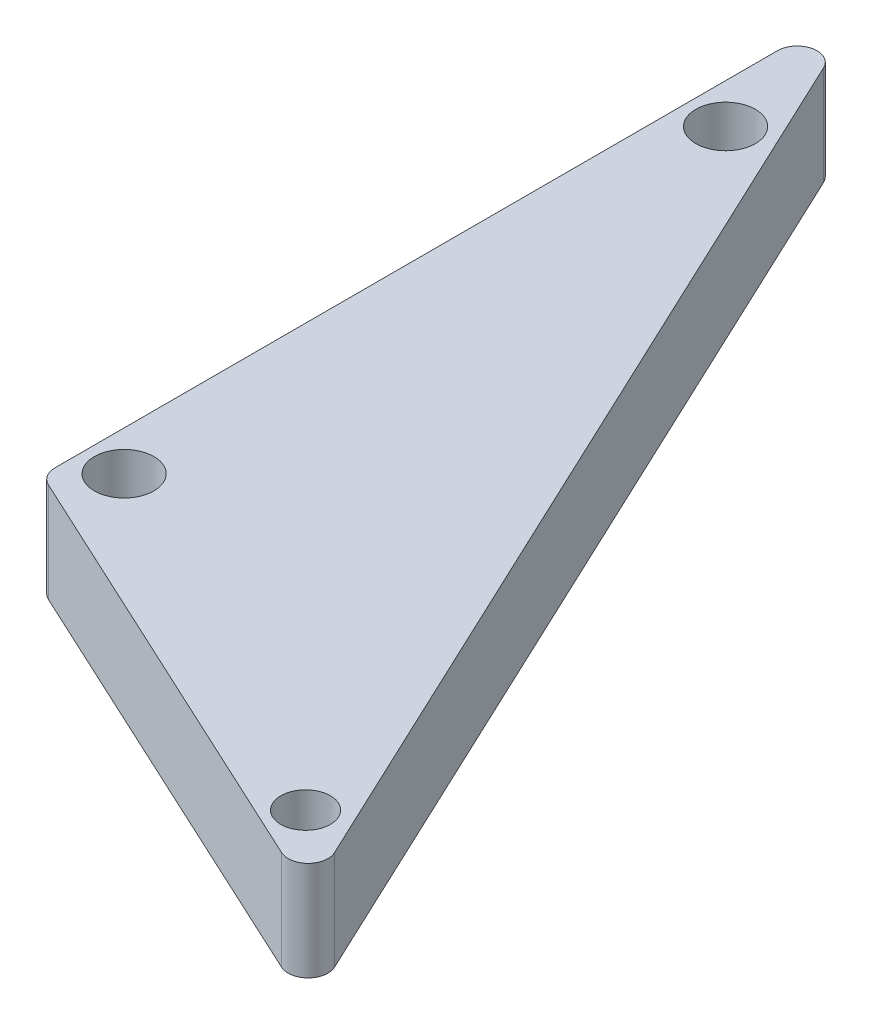
SolidWorks part; units mm, degrees
ref_plane "Front Plane" through (0, 0, 0) normal (0, 0, 1) x (1, 0, 0)
ref_plane "Top Plane" through (0, 0, 0) normal (0, 1, 0) x (1, 0, 0)
ref_plane "Right Plane" through (0, 0, 0) normal (1, 0, 0) x (0, 0, -1)
sketch "Sketch1" plane through (0, 0, 0) normal (0, 1, 0) x (1, 0, 0)
  line L0 (0, 0) -> (0, 105.41)
  line L3 (0, 0) -> (0, -29.464) construction
  line L4 (0, -29.464) -> (63.5, -29.464) construction
  line L5 (0, 105.41) -> (63.5, -29.464)
  line L6 (63.5, -29.464) -> (0, 0)
  dimension "D1" = 105.41
  dimension "D3" = 29.464
extrude "Boss-Extrude1" add sketch "Sketch1" along normal blind 12.7
sketch "Sketch2" plane through (0, 0, 0) normal (0, -1, 0) x (1, 0, 0)
  line L0 (5.08, -103.9192) -> (5.08, 20.2615) construction
  line L1 (0, -105.41) -> (0, 0) construction
  circle A0 centre (5.08, -82.3472) radius 3.81
  circle A1 centre (5.08, -5.3956) radius 3.81
  circle A2 centre (53.9557, 20.2615) radius 3.175
  dimension "D2" = 7.62
  dimension "D3" = 7.62
  dimension "D4" = 6.35
  dimension "D1" = 5.08
extrude "Cut-Extrude1" cut sketch "Sketch2" against normal through all
fillet "Fillet1" radius 2.54 3 edges at (0, 6.35, 0) (0, 6.35, -105.41) (63.5, 6.35, 29.464)
